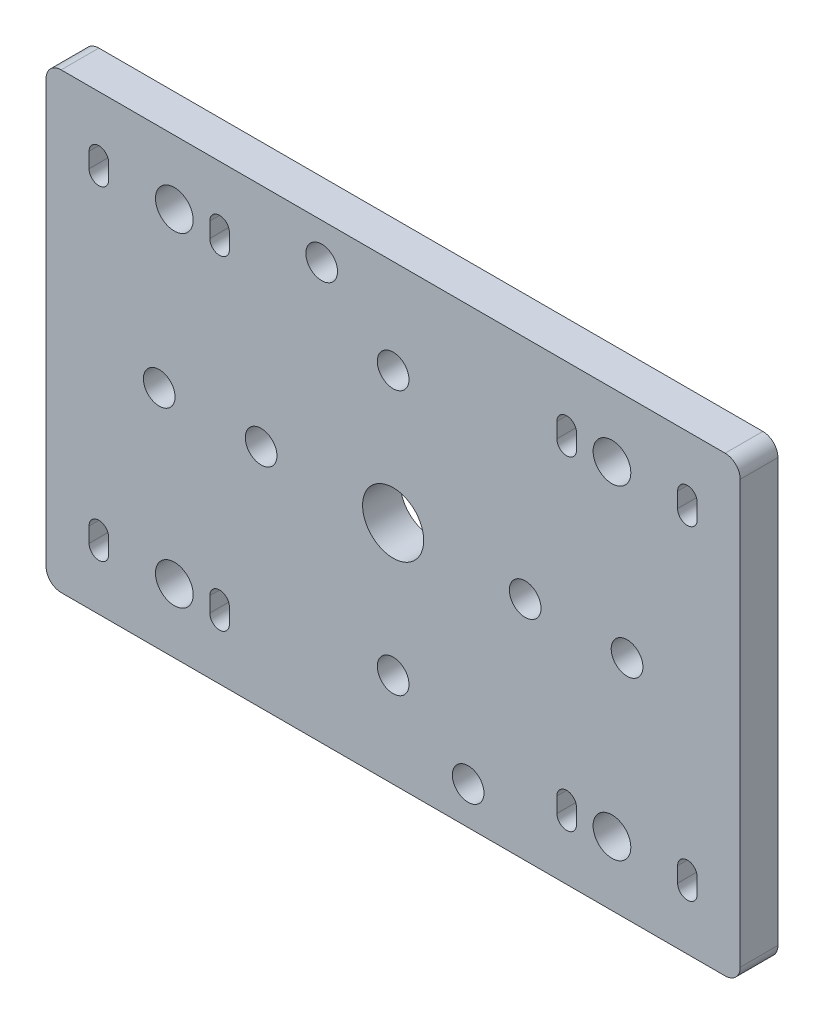
SolidWorks part; units mm, degrees
ref_plane "Front Plane" through (0, 0, 0) normal (0, 0, 1) x (1, 0, 0)
ref_plane "Top Plane" through (0, 0, 0) normal (0, 1, 0) x (1, 0, 0)
ref_plane "Right Plane" through (0, 0, 0) normal (1, 0, 0) x (0, 0, -1)
sketch "Sketch1" plane through (0, 0, 0) normal (0, 0, 1) x (1, 0, 0)
  line L0 (39, 20.5) -> (39, 22.5) construction
  line L1 (-46, -30) -> (46, -30)
  line L2 (-46, -30) -> (-46, 30)
  line L3 (-46, 30) -> (46, 30)
  line L4 (46, -30) -> (46, 30)
  line L5 (0, 30) -> (0, -30) construction
  line L6 (-46, 0) -> (46, 0) construction
  line L7 (-17.5, -17.5) -> (17.5, -17.5)
  line L8 (-17.5, -17.5) -> (-17.5, 17.5)
  line L9 (-17.5, 17.5) -> (17.5, 17.5)
  line L10 (17.5, -17.5) -> (17.5, 17.5)
  line L11 (0, 17.5) -> (0, -17.5) construction
  line L12 (-17.5, 0) -> (17.5, 0) construction
  line L13 (37.7, 20.5) -> (37.7, 22.5)
  line L14 (40.3, 20.5) -> (40.3, 22.5)
  line L15 (23, 20.5) -> (23, 22.5) construction
  line L16 (21.7, 20.5) -> (21.7, 22.5)
  line L17 (24.3, 20.5) -> (24.3, 22.5)
  line L18 (39, -20.5) -> (39, -22.5) construction
  line L19 (37.7, -20.5) -> (37.7, -22.5)
  line L20 (40.3, -20.5) -> (40.3, -22.5)
  line L21 (23, -20.5) -> (23, -22.5) construction
  line L22 (21.7, -20.5) -> (21.7, -22.5)
  line L23 (24.3, -20.5) -> (24.3, -22.5)
  line L24 (-23, -20.5) -> (-23, -22.5) construction
  line L25 (-21.7, -20.5) -> (-21.7, -22.5)
  line L26 (-24.3, -20.5) -> (-24.3, -22.5)
  line L27 (-39, -20.5) -> (-39, -22.5) construction
  line L28 (-37.7, -20.5) -> (-37.7, -22.5)
  line L29 (-40.3, -20.5) -> (-40.3, -22.5)
  line L30 (-23, 20.5) -> (-23, 22.5) construction
  line L31 (-21.7, 20.5) -> (-21.7, 22.5)
  line L32 (-24.3, 20.5) -> (-24.3, 22.5)
  line L33 (-39, 20.5) -> (-39, 22.5) construction
  line L34 (-37.7, 20.5) -> (-37.7, 22.5)
  line L35 (-40.3, 20.5) -> (-40.3, 22.5)
  circle A0 centre (0, 0) radius 4.05
  circle A1 centre (0, 17.5) radius 2.1
  circle A2 centre (0, -17.5) radius 2.1
  circle A3 centre (-17.5, 0) radius 2.1
  circle A4 centre (17.5, 0) radius 2.1
  circle A5 centre (29, 21.5) radius 2.5
  arc A6 (37.7, 20.5) -> (40.3, 20.5) centre (39, 20.5) ccw
  arc A7 (40.3, 22.5) -> (37.7, 22.5) centre (39, 22.5) ccw
  arc A8 (21.7, 20.5) -> (24.3, 20.5) centre (23, 20.5) ccw
  arc A9 (24.3, 22.5) -> (21.7, 22.5) centre (23, 22.5) ccw
  arc A10 (37.7, -20.5) -> (40.3, -20.5) centre (39, -20.5) cw
  arc A11 (40.3, -22.5) -> (37.7, -22.5) centre (39, -22.5) cw
  circle A12 centre (29, -21.5) radius 2.5
  arc A13 (21.7, -20.5) -> (24.3, -20.5) centre (23, -20.5) cw
  arc A14 (24.3, -22.5) -> (21.7, -22.5) centre (23, -22.5) cw
  arc A15 (-21.7, -20.5) -> (-24.3, -20.5) centre (-23, -20.5) ccw
  arc A16 (-24.3, -22.5) -> (-21.7, -22.5) centre (-23, -22.5) ccw
  circle A17 centre (-29, -21.5) radius 2.5
  arc A18 (-37.7, -20.5) -> (-40.3, -20.5) centre (-39, -20.5) ccw
  arc A19 (-40.3, -22.5) -> (-37.7, -22.5) centre (-39, -22.5) ccw
  arc A20 (-21.7, 20.5) -> (-24.3, 20.5) centre (-23, 20.5) cw
  arc A21 (-24.3, 22.5) -> (-21.7, 22.5) centre (-23, 22.5) cw
  circle A22 centre (-29, 21.5) radius 2.5
  arc A23 (-37.7, 20.5) -> (-40.3, 20.5) centre (-39, 20.5) cw
  arc A24 (-40.3, 22.5) -> (-37.7, 22.5) centre (-39, 22.5) cw
  circle A25 centre (-31, 0) radius 2.1
  circle A26 centre (31, 0) radius 2.1
  circle A27 centre (9.941, -25) radius 2.1
  circle A28 centre (-9.4664, 25.1669) radius 2.1
  point P0 (0, 0)
  point P17 (39, 21.5)
  point P24 (23, 21.5)
  point P31 (39, -21.5)
  point P40 (23, -21.5)
  point P47 (-23, -21.5)
  point P62 (-39, -21.5)
  point P69 (-23, 21.5)
  point P78 (-39, 21.5)
  dimension "D3" = 8.1
  dimension "D6" = 4.2
  dimension "D11" = 1.3
  dimension "D13" = 5
  dimension "D15" = 1.3
  dimension "D9" = 4.2
  dimension "D1" = 92
  dimension "D2" = 60
  dimension "D4" = 17.5
  dimension "D5" = 17.5
  dimension "D7" = 7
  dimension "D8" = 8.5
  dimension "D10" = 10
  dimension "D12" = 2
  dimension "D14" = 2
  dimension "D16" = 31
  dimension "D17" = 31
extrude "Boss-Extrude1" add sketch "Sketch1" along normal mid plane 5 contours A4 L10 L9 A1 L8 A3 L7 A2 A0 | L1 L4 L3 L2 A4 L10 L7 A2 L8 A3 L9 A1
fillet "Fillet1" radius 2 4 edges at (-46, -30, 0) (46, -30, 0) (46, 30, 0) (-46, 30, 0)
